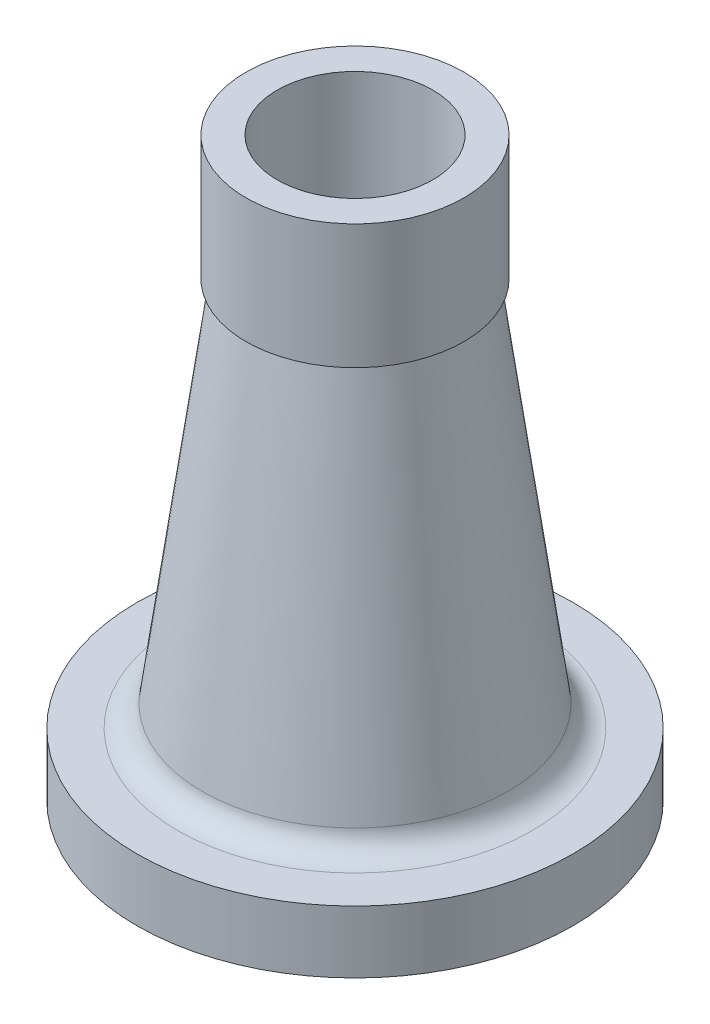
SolidWorks part; units mm, degrees
material "Malleable Cast Iron"
ref_plane "Front Plane" through (0, 0, 0) normal (0, 0, 1) x (1, 0, 0)
ref_plane "Top Plane" through (0, 0, 0) normal (0, 1, 0) x (1, 0, 0)
ref_plane "Right Plane" through (0, 0, 0) normal (1, 0, 0) x (0, 0, -1)
sketch "Sketch2" plane through (0, 0, 0) normal (0, 0, 1) x (1, 0, 0)
  line L0 (0, 0) -> (0, 185) construction
  line L1 (50, 0) -> (70, 0)
  line L2 (70, 0) -> (70, 20)
  line L3 (70, 20) -> (50, 20)
  line L4 (50, 0) -> (50, 3)
  line L5 (50, 3) -> (42.2199, 3)
  line L6 (25, 185) -> (25, 129.6172)
  line L7 (25, 185) -> (35, 185)
  line L8 (35, 185) -> (35, 145)
  line L9 (35, 145) -> (33, 145)
  line L10 (33, 145) -> (50, 20)
  line L11 (25, 129.6172) -> (42.2199, 3)
  line L12 (23.0912, 143.6524) -> (40.0912, 18.6524) construction
  dimension "D1" = 185
  dimension "D2" = 50
  dimension "D3" = 70
  dimension "D4" = 20
  dimension "D5" = 25
  dimension "D6" = 35
  dimension "D7" = 40
  dimension "D8" = 2
  dimension "D10" = 3
  dimension "D9" = 10
revolve "Revolve2" add sketch "Sketch2" angle 360 about L0
fillet "Fillet1" radius 8 1 edges at (0, 20, -50)
fillet "Fillet2" radius 1 1 edges at (0, 145, -33)
